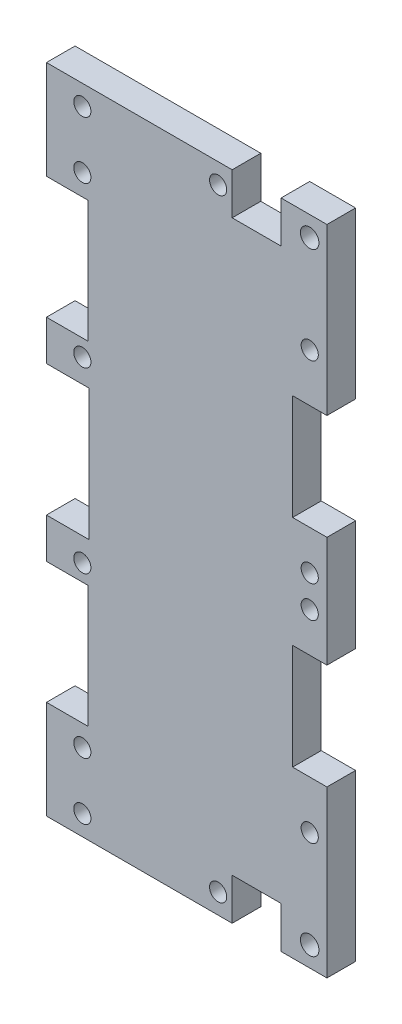
SolidWorks part; units mm, degrees
ref_plane "前视基准面" through (0, 0, 0) normal (0, 0, 1) x (1, 0, 0)
ref_plane "上视基准面" through (0, 0, 0) normal (0, 1, 0) x (1, 0, 0)
ref_plane "右视基准面" through (0, 0, 0) normal (1, 0, 0) x (0, 0, -1)
sketch "草图1" plane through (0, 0, 0) normal (0, 0, 1) x (1, 0, 0)
  line L1 (-118, 210) -> (118, 210)
  line L2 (-118, 210) -> (-118, -210)
  line L3 (-118, -210) -> (118, -210)
  line L4 (118, 210) -> (118, 50.5)
  line L5 (-118, 210) -> (118, -210) construction
  line L6 (-118, -210) -> (118, 210) construction
  line L7 (118, -50.5) -> (54.15, -50.5)
  line L12 (54.15, -9.3341) -> (54.15, -50.5)
  line L14 (118, -50.5) -> (118, -210)
  line L17 (54.15, 50.5) -> (118, 50.5)
  line L22 (0, 0) -> (61, 0) construction
  line L24 (79, 0) -> (133.002, 0) construction
  line L59 (54.15, 9.3341) -> (54.15, 50.5)
  arc A22 (54.15, 9.3341) -> (54.3482, -9.2794) centre (51.6769, 0) ccw
  point P0 (0, 0)
  point P9 (118, 0)
  dimension "D3" = 63.85
  dimension "D1" = 236
  dimension "D2" = 420
extrude "凸台-拉伸1" add sketch "草图1" along normal blind 10
sketch "草图2" plane through (0, 0, 10) normal (0, 0, 1) x (1, 0, 0)
  line L0 (-118, 210) -> (-118, -210) construction
  line L2 (-88, 135) -> (-88, 180) construction
  line L3 (-88, 180) -> (-43, 180) construction
  line L5 (-88, 135) -> (-43, 180) construction
  line L7 (-118, 210) -> (118, 210) construction
  circle A0 centre (-88, 135) radius 1.5
  circle A1 centre (-43, 180) radius 1.5
  circle A2 centre (-88, 180) radius 1.5
  point P0 (-65.5, 157.5)
  dimension "D1" = 45
  dimension "D2" = 45
  dimension "D3" = 30
  dimension "D4" = 30
extrude "切除-拉伸1" cut sketch "草图2" against normal blind 10
sketch "草图3" plane through (0, 0, 10) normal (0, 0, 1) x (1, 0, 0)
  line L1 (54.15, -9.3341) -> (54.15, -50.5) construction
  line L2 (54.15, -9.3341) -> (54.15, -50.5) construction
  line L3 (0, 0) -> (125.1957, 0) construction
  line L4 (112.73, -53.5) -> (112.73, -59.5) construction
  line L5 (112.73, -59.5) -> (87.23, -59.5) construction
  line L6 (87.23, -59.5) -> (87.23, -53.5) construction
  line L7 (87.23, -53.5) -> (77.23, -53.5) construction
  line L8 (77.23, -53.5) -> (61.23, -53.5) construction
  line L9 (61.23, -53.5) -> (51.15, -53.5) construction
  line L10 (51.15, -53.5) -> (51.15, -43.5) construction
  line L11 (87.23, -53.5) -> (112.73, -53.5) construction
  line L12 (118, -50.5) -> (54.15, -50.5) construction
  line L13 (118, -50.5) -> (118, -210) construction
  circle A1 centre (51.15, -15.6728) radius 1.5
  circle A2 centre (112.73, -53.5) radius 1.5
  circle A3 centre (112.73, -59.5) radius 1.5
  circle A4 centre (87.23, -53.5) radius 1.5
  circle A5 centre (87.23, -59.5) radius 1.5
  circle A6 centre (77.23, -53.5) radius 1.5
  circle A7 centre (61.23, -53.5) radius 1.5
  circle A8 centre (51.15, -53.5) radius 1.5
  circle A9 centre (51.15, -43.5) radius 1.5
  dimension "D2" = 3
  dimension "D4" = 3
  dimension "D5" = 3
  dimension "D6" = 3
  dimension "D7" = 3
  dimension "D8" = 3
  dimension "D9" = 3
  dimension "D10" = 3
  dimension "D11" = 3
  dimension "D3" = 3
  dimension "D12" = 3
  dimension "D13" = 5.27
  dimension "D14" = 25.5
  dimension "D15" = 10
  dimension "D16" = 6
  dimension "D17" = 16
  dimension "D18" = 3
  dimension "D19" = 10
extrude "切除-拉伸2" cut sketch "草图3" against normal blind 10
mirror "镜向1" about plane through (0, 0, 0) normal (0, 1, 0) of "切除-拉伸2"
ref_plane "基准面1" through (0, 0, 20) normal (0, 0, 1) x (1, 0, 0)
sketch "草图5" plane through (0, 0, 20) normal (0, 0, 1) x (1, 0, 0)
  line L0 (0, 0) -> (104.5416, 0) construction
  line L1 (32.8886, 57.01) -> (81.8986, 57.01)
  line L2 (32.8886, 57.01) -> (32.8886, -57.01)
  line L3 (32.8886, -57.01) -> (81.8986, -57.01)
  line L4 (81.8986, 57.01) -> (81.8986, -57.01)
  dimension "D1" = 114.02
  dimension "D2" = 57.01
  dimension "D3" = 49.01
extrude "凸台-拉伸2" add sketch "草图5" along normal blind 5 separate body
sketch "草图7" plane through (0, 0, 25) normal (0, 0, 1) x (1, 0, 0)
  line L0 (32.5827, 39.8) -> (40.1627, 39.8)
  line L1 (32.5827, 39.8) -> (32.005, 39.8) construction
  line L2 (40.1627, 39.8) -> (40.1627, 18.4749)
  line L3 (40.1627, 18.4749) -> (32.5827, 18.4749)
  line L4 (32.5827, 18.4749) -> (32.5827, 39.8)
  line L5 (32.7128, 11.46) -> (40.2928, 11.46)
  line L6 (40.2928, 11.46) -> (40.2928, -0.3181)
  line L7 (40.2928, -0.3181) -> (32.7128, -0.3181)
  line L8 (32.7128, -0.3181) -> (32.7128, 11.46)
  line L9 (54.15, 9.3341) -> (54.15, 50.5)
  line L10 (54.15, 50.5) -> (118, 50.5)
  line L11 (118, 50.5) -> (118, 210)
  line L12 (118, 210) -> (-118, 210)
  line L13 (-118, 210) -> (-118, -210)
  line L14 (-118, -210) -> (118, -210)
  line L15 (118, -210) -> (118, -50.5)
  line L16 (118, -50.5) -> (54.15, -50.5)
  line L17 (54.15, -50.5) -> (54.15, -9.3341)
  line L20 (118, 50.5) -> (118, 210)
  line L21 (118, 210) -> (-118, 210)
  line L22 (-118, 210) -> (-118, -210)
  line L23 (-118, -210) -> (118, -210)
  line L24 (118, -210) -> (118, -50.5)
  line L27 (65.3379, 57.155) -> (65.3379, 49.7352)
  line L29 (65.3379, 49.7352) -> (73.8808, 49.7352)
  line L30 (73.8808, 49.7352) -> (73.8808, 57.155)
  line L31 (73.8808, 57.155) -> (65.3379, 57.155)
  line L33 (81.8986, 57.01) -> (32.8886, 57.01) construction
  arc A1 (54.15, 9.3341) -> (54.15, -9.3341) centre (51.6769, 0) ccw
  line M11 (32.8886, 57.01) -> (32.8886, -57.01)
  line M14 (81.8986, 57.01) -> (32.8886, 57.01)
  dimension "D2" = 17.21
  dimension "D3" = 45.55
  dimension "D1" = 0
extrude "切除-拉伸3" cut sketch "草图7" against normal blind 10 contours L3 L2 L0 M11 | L7 L6 L5 M11 | L29 L30 L27 M14
mirror "镜向2" about plane through (0, 0, 0) normal (0, 1, 0) of "切除-拉伸3"
delete or keep bodies "实体-删除/保留 1" type delete bodies bodies 104
sketch "草图8" plane through (0, 0, 25) normal (0, 0, 1) x (1, 0, 0)
  line L0 (81.8986, 28.1008) -> (75.8986, 28.1008)
  line L2 (75.8986, 28.1008) -> (75.8986, 9.6743)
  line L3 (75.8986, 9.6743) -> (81.8986, 9.6743)
  line L4 (81.8986, 9.6743) -> (81.8986, 28.1008)
  dimension "D4" = 6
extrude "切除-拉伸4" cut sketch "草图8" against normal blind 10
mirror "镜向3" about plane through (0, 0, 0) normal (0, 1, 0) of "切除-拉伸4"
sketch "草图9" plane through (0, 0, 25) normal (0, 0, 1) x (1, 0, 0)
  line L0 (39.1586, 53.5) -> (62.8886, 53.5) construction
  line L1 (39.1586, 53.5) -> (39.1586, 43.5) construction
  line L2 (32.8886, 57.01) -> (32.8886, 39.8) construction
  line L3 (65.3379, 57.01) -> (32.8886, 57.01) construction
  line L4 (62.8886, 53.5) -> (78.8808, 53.5) construction
  line L5 (73.8808, 49.7352) -> (73.8808, 57.01) construction
  line L6 (39.1586, 43.5) -> (39.1586, 15.5649) construction
  line L7 (81.8986, 28.1008) -> (81.8986, 57.01) construction
  line L8 (81.8986, 28.1008) -> (75.8986, 28.1008) construction
  line L9 (78.8886, 36.5108) -> (78.8886, 2.7752) construction
  line L10 (40.1627, 18.4749) -> (32.8886, 18.4749) construction
  line L12 (65.3379, 49.7352) -> (73.8808, 49.7352) construction
  circle A0 centre (39.1586, 53.5) radius 1.5
  circle A1 centre (62.8886, 53.5) radius 1.5
  circle A2 centre (39.1586, 43.5) radius 1.5
  circle A3 centre (78.8808, 53.5) radius 1.6218
  circle A4 centre (39.1586, 15.5649) radius 1.5
  circle A6 centre (78.8886, 36.5108) radius 1.5
  circle A7 centre (78.8886, 2.7752) radius 1.5
  dimension "D1" = 3
  dimension "D2" = 3
  dimension "D3" = 3
  dimension "D7" = 3
  dimension "D9" = 3
  dimension "D14" = 3
  dimension "D4" = 6.27
  dimension "D5" = 3.51
  dimension "D6" = 5
  dimension "D8" = 2.91
  dimension "D10" = 3.01
  dimension "D11" = 23.73
  dimension "D12" = 10
  dimension "D13" = 8.41
  dimension "D15" = 46.96
extrude "切除-拉伸5" cut sketch "草图9" against normal blind 10
mirror "镜向5" about plane through (0, 0, 0) normal (0, 1, 0) of "切除-拉伸5"
